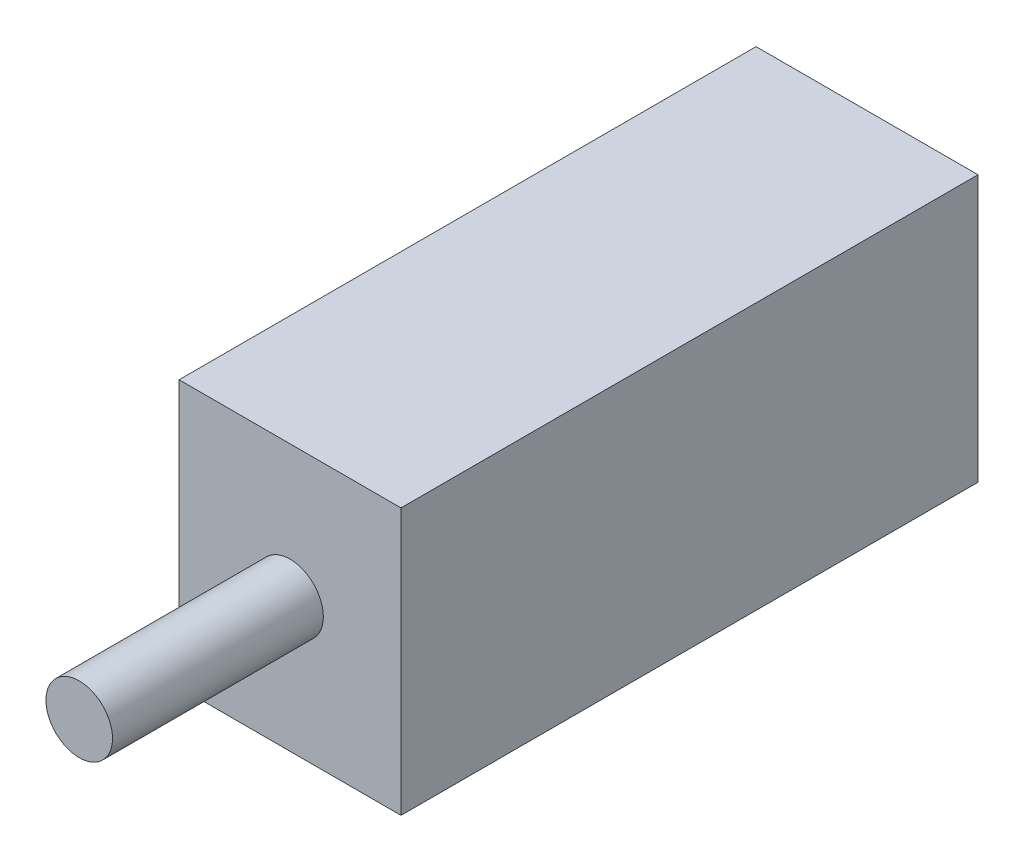
SolidWorks part; units mm, degrees
ref_plane "Front Plane" through (0, 0, 0) normal (0, 0, 1) x (1, 0, 0)
ref_plane "Top Plane" through (0, 0, 0) normal (0, 1, 0) x (1, 0, 0)
ref_plane "Right Plane" through (0, 0, 0) normal (1, 0, 0) x (0, 0, -1)
sketch "Sketch2" plane through (0, 0, 0) normal (0, 0, 1) x (1, 0, 0)
  line L1 (0, 0) -> (10, 0)
  line L2 (0, 0) -> (0, 12)
  line L3 (0, 12) -> (10, 12)
  line L4 (10, 0) -> (10, 12)
  dimension "D1" = 10
  dimension "D2" = 12
extrude "Boss-Extrude1" add sketch "Sketch2" along normal blind 26
sketch "Sketch3" plane through (0, 0, 26) normal (0, 0, 1) x (1, 0, 0)
  line L0 (0, 12) -> (0, 0) construction
  line L1 (0, 0) -> (10, 0) construction
  circle A0 centre (5, 6) radius 1.5
  dimension "D1" = 3
  dimension "D2" = 5
  dimension "D3" = 6
extrude "Boss-Extrude2" add sketch "Sketch3" along normal blind 9.5
